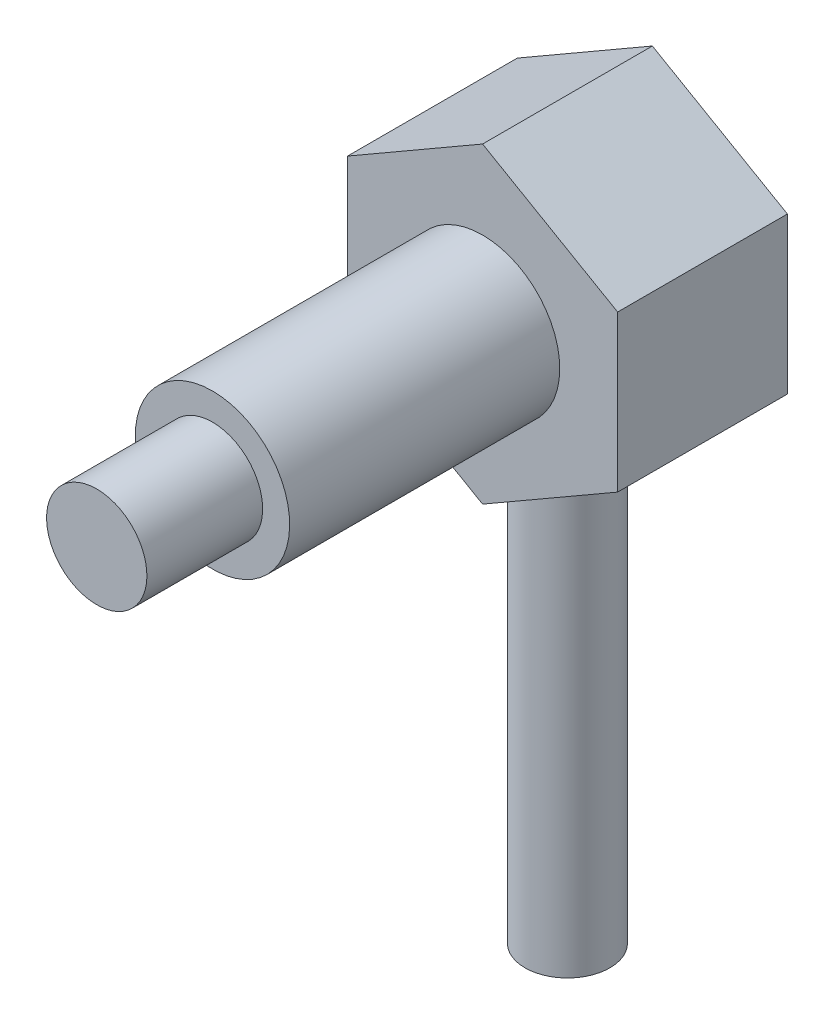
SolidWorks part; units mm, degrees
ref_plane "Front" through (0, 0, 0) normal (0, 0, 1) x (1, 0, 0)
ref_plane "Top" through (0, 0, 0) normal (0, 1, 0) x (1, 0, 0)
ref_plane "Right" through (0, 0, 0) normal (1, 0, 0) x (0, 0, -1)
sketch "Sketch1" plane through (0, 0, 0) normal (0, 0, 1) x (1, 0, 0)
  line L1 (3.5, -2.0207) -> (3.5, 2.0207)
  line L2 (3.5, 2.0207) -> (0, 4.0415)
  line L3 (0, 4.0415) -> (-3.5, 2.0207)
  line L4 (-3.5, 2.0207) -> (-3.5, -2.0207)
  line L5 (-3.5, -2.0207) -> (0, -4.0415)
  line L6 (0, -4.0415) -> (3.5, -2.0207)
  circle A0 centre (0, 0) radius 3.5 construction
  dimension "D1" = 7
extrude "Extrude1" add sketch "Sketch1" along normal blind 4.4
sketch "Sketch2" plane through (0, 0, 0) normal (1, 0, 0) x (0, 0, -1)
  line L0 (-4.4, 0) -> (-14.4, 0) construction
  line L1 (-4.4, -2.0207) -> (-4.4, 2.0207) construction
  line L2 (-14.4, 0) -> (-14.4, 1.3)
  line L3 (-14.4, 1.3) -> (-11.4, 1.3)
  line L4 (-11.4, 1.3) -> (-11.4, 2)
  line L5 (-11.4, 2) -> (-4.4, 2)
  line L6 (-4.4, 2.0207) -> (-4.4, 4.0415) construction
  line L7 (-4.4, 2) -> (-4.4, 0)
  line L8 (-4.4, 0) -> (-14.4, 0)
  dimension "D1" = 2.6
  dimension "D2" = 4
  dimension "D3" = 3
  dimension "D4" = 7
revolve "Revolve1" add sketch "Sketch2" angle 360 about L0
cosmetic thread "Cosmetic Thread1" parameters "D1"=7, "D2"=3
sketch "Sketch3" plane through (0, 0, 0) normal (0, 1, 0) x (1, 0, 0)
  line L0 (0, -4.4) -> (0, 0) construction
  circle A0 centre (0, -2.2) radius 1.1
  dimension "D1" = 2.2
extrude "Extrude2" add sketch "Sketch3" against normal blind 15
